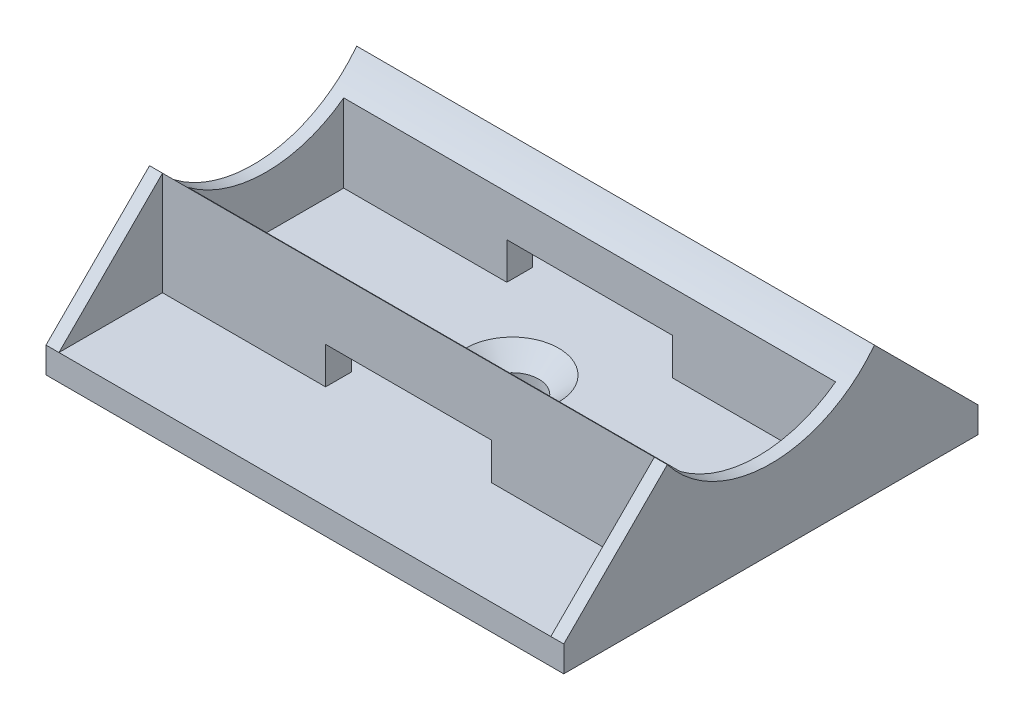
SolidWorks part; units mm, degrees
ref_plane "Front Plane" through (0, 0, 0) normal (0, 0, 1) x (1, 0, 0)
ref_plane "Top Plane" through (0, 0, 0) normal (0, 1, 0) x (1, 0, 0)
ref_plane "Right Plane" through (0, 0, 0) normal (1, 0, 0) x (0, 0, -1)
sketch "Sketch4" plane through (0, 0, 0) normal (1, 0, 0) x (0, 0, -1)
  line L1 (0, 0) -> (25.4, 0)
  line L2 (0, 0) -> (0, 1.5875)
  line L3 (0, 1.5875) -> (25.4, 1.5875)
  line L4 (25.4, 0) -> (25.4, 1.5875)
  line L5 (7.9375, 7.9375) -> (6.35, 7.9375)
  line L6 (7.9375, 7.9375) -> (7.9375, 1.5875)
  line L7 (7.9375, 1.5875) -> (6.35, 1.5875)
  line L8 (6.35, 7.9375) -> (6.35, 1.5875)
  line L9 (17.4625, 7.9375) -> (19.05, 7.9375)
  line L10 (17.4625, 7.9375) -> (17.4625, 1.5875)
  line L11 (17.4625, 1.5875) -> (19.05, 1.5875)
  line L12 (19.05, 7.9375) -> (19.05, 1.5875)
extrude "Boss-Extrude2" add sketch "Sketch4" along normal blind 31.75 contours L1 L4 L3 L2 | L5 L8 L3 L6 | L12 L9 L10 L3
sketch "Sketch5" plane through (31.75, 0, 0) normal (1, 0, 0) x (0, 0, -1)
  line L0 (6.35, 7.9375) -> (0, 1.5875)
  line L1 (0, 1.5875) -> (6.35, 1.5875)
  line L2 (6.35, 1.5875) -> (6.35, 7.9375)
  line L3 (7.9375, 7.9375) -> (17.4625, 7.9375)
  line L4 (17.4625, 7.9375) -> (17.4625, 1.5875) construction
  line L5 (17.4625, 7.9375) -> (17.4625, 1.5875)
  line L6 (17.4625, 1.5875) -> (7.9375, 1.5875)
  line L7 (7.9375, 1.5875) -> (7.9375, 7.9375)
  line L8 (19.05, 7.9375) -> (19.05, 1.5875)
  line L9 (19.05, 1.5875) -> (25.4, 1.5875)
  line L10 (25.4, 1.5875) -> (19.05, 7.9375)
extrude "Boss-Extrude3" add sketch "Sketch5" against normal blind 0.7937
sketch "Sketch6" plane through (0, 0, 0) normal (-1, 0, 0) x (0, 0, 1)
  line L0 (-25.4, 1.5875) -> (0, 1.5875)
  line L1 (0, 1.5875) -> (-6.35, 7.9375)
  line L2 (-6.35, 7.9375) -> (-19.05, 7.9375)
  line L3 (-19.05, 7.9375) -> (-25.4, 1.5875)
extrude "Boss-Extrude4" add sketch "Sketch6" against normal blind 0.7937
sketch "Sketch7" plane through (0, 0, -6.35) normal (0, 0, 1) x (1, 0, 0)
  line L0 (30.9563, 1.5875) -> (0.7937, 1.5875) construction
  line L1 (20.955, 1.5875) -> (10.795, 1.5875)
  line L2 (20.955, 1.5875) -> (20.955, 3.848)
  line L3 (20.955, 3.848) -> (10.795, 3.848)
  line L4 (10.795, 1.5875) -> (10.795, 3.848)
extrude "Cut-Extrude1" cut sketch "Sketch7" against normal through all
sketch "Sketch8" plane through (31.75, 0, 0) normal (1, 0, 0) x (0, 0, -1)
  circle A0 centre (12.7, 12.8219) radius 8.0112
extrude "Cut-Extrude2" cut sketch "Sketch8" against normal up to next
hole_wizard "CSK for #4 Flat Head Machine Screw (100)1" positions "Sketch13" profile "Sketch10" countersink size "#4" standard "ANSI Inch" end condition through all
sketch "Sketch13" plane through (0, 1.5875, 0) normal (0, 1, 0) x (1, 0, 0)
  point P0 (15.8873, 12.6978)
sketch "Sketch10" plane through (15.8873, 1.5875, -12.6978) normal (1, 0, 0) x (0, 0, 1)
  line L0 (0, 0) -> (0, 1.5875)
  line L1 (0, 1.5875) -> (1.6319, 1.5875)
  line L2 (1.6319, 1.5875) -> (1.6319, 1.0284)
  line L3 (1.6319, 1.0284) -> (2.8575, 0)
  line L5 (2.8575, 0) -> (0, 0)
  line L6 (-1.6319, 1.0284) -> (-2.8575, 0) construction
  line L11 (0, -6.35) -> (0, 107.95) construction
  dimension "Thru Hole Dia." = 3.2639
  dimension "Thru Hole Depth" = 1.5875
  dimension "Near C'Sink Dia." = 5.715
  dimension "Near C'Sink Angle" = 100
